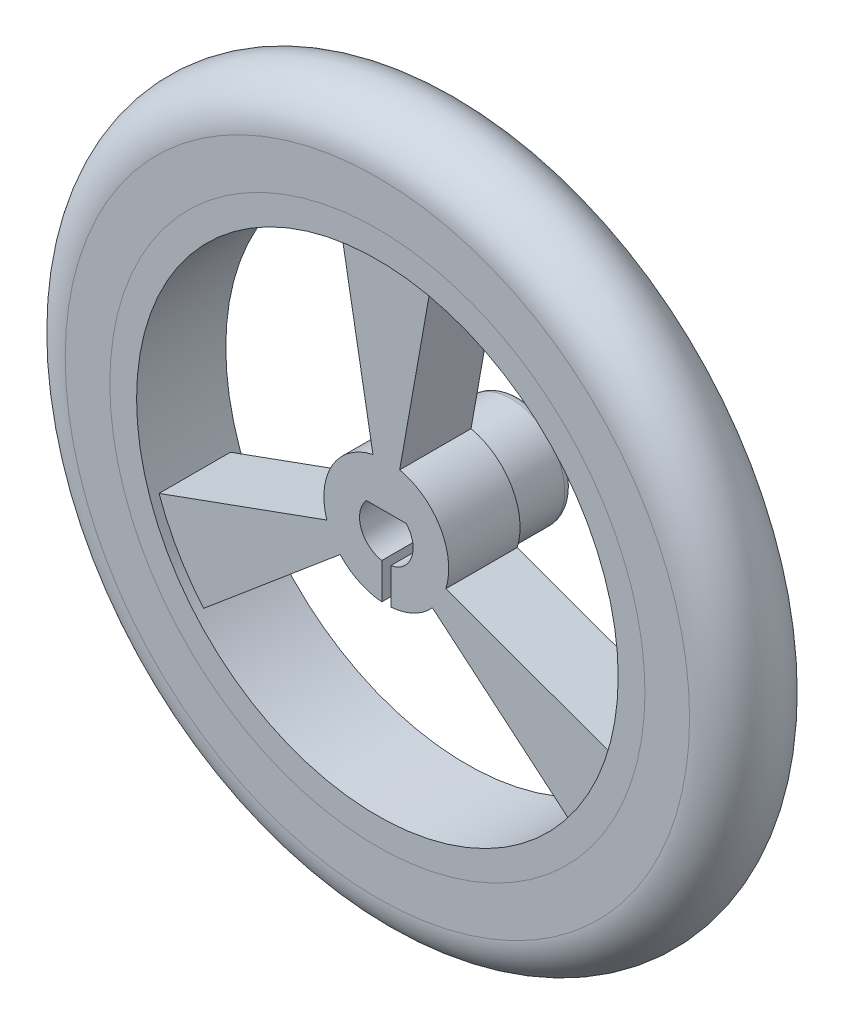
SolidWorks part; units mm, degrees
other "tire"
other "wheel"
ref_plane "Přední rovina" through (0, 0, 0) normal (0, 0, 1) x (1, 0, 0)
ref_plane "Horní rovina" through (0, 0, 0) normal (0, 1, 0) x (1, 0, 0)
ref_plane "Pravá rovina" through (0, 0, 0) normal (1, 0, 0) x (0, 0, -1)
sketch "Skica2" plane through (0, 0, 0) normal (1, 0, 0) x (0, 0, -1)
  line L0 (-2, 13.5) -> (-2, 0)
  line L1 (-1, 18) -> (1, 18)
  line L2 (1, 18) -> (1, 15)
  line L3 (1, 15) -> (2.5, 15)
  line L4 (2.5, 15) -> (2.5, 13.5)
  line L5 (2.5, 13.5) -> (2, 13.5)
  line L6 (5.5, 0) -> (-2, 0)
  line L7 (2, 13.5) -> (2, 3)
  line L8 (2, 3) -> (5, 3)
  line L9 (5.5, 2.5) -> (5.5, 0)
  line L10 (-36.9889, 0) -> (36.9889, 0) construction
  line L11 (0, 0) -> (0, 62.8313) construction
  line L13 (-2.5, 13.5) -> (-2, 13.5)
  line L14 (-2.5, 15) -> (-2.5, 13.5)
  line L15 (-1, 15) -> (-2.5, 15)
  line L16 (-1, 18) -> (-1, 15)
  arc A0 (5, 3) -> (5.5, 2.5) centre (5, 2.5) cw
  point P22 (0, 18)
  dimension "D9" = 0.5
  dimension "D1" = 36
  dimension "D2" = 5
  dimension "D3" = 3
  dimension "D4" = 4
  dimension "D5" = 1.5
  dimension "D6" = 6
  dimension "D7" = 8
  dimension "D8" = 1.5
revolve "Rotovat1" add sketch "Skica2" angle 360 about L10
sketch "Skica3" plane through (0, 0, 2) normal (0, 0, 1) x (1, 0, 0)
  line L0 (12.7391, -4.4682) -> (3.3357, -1.0598)
  line L1 (0, 0) -> (0, 29.5863) construction
  line L2 (-2.5, 13.2665) -> (-0.75, 3.4187)
  line L3 (10.2391, -8.7983) -> (2.5857, -2.3589)
  line L4 (-10.2391, -8.7983) -> (-2.5857, -2.3589)
  line L5 (-12.7391, -4.4682) -> (-3.3357, -1.0598)
  line L9 (2.5, 13.2665) -> (0.75, 3.4187)
  circle A0 centre (0, 0) radius 13.5 construction
  arc A1 (12.7391, -4.4682) -> (2.5, 13.2665) centre (0, 0) ccw
  arc A2 (-2.5, 13.2665) -> (-12.7391, -4.4682) centre (0, 0) ccw
  arc A3 (3.3357, -1.0598) -> (0.75, 3.4187) centre (0, 0) ccw
  arc A4 (-2.5857, -2.3589) -> (2.5857, -2.3589) centre (0, 0) ccw
  arc A5 (-10.2391, -8.7983) -> (10.2391, -8.7983) centre (0, 0) ccw
  arc A29 (-0.75, 3.4187) -> (-3.3357, -1.0598) centre (0, 0) ccw
  point P10 (-0.75, 3.4187)
  point P13 (0.75, 3.4187)
  dimension "D1" = 7
  dimension "D2" = 1.5
  dimension "D4" = 3
  dimension "D3" = 5
extrude "Odebrat vysunutím1" cut sketch "Skica3" against normal through all
sketch "Skica4" plane through (0, 0, 2) normal (0, 0, 1) x (1, 0, 0)
  line L0 (-1.118, 1) -> (1.118, 1)
  line L1 (0, 0) -> (0, -11.6723) construction
  line L2 (-0.25, -1.479) -> (-0.25, -4.8326)
  line L3 (0.25, -1.479) -> (0.25, -4.8326)
  line L4 (-0.25, -4.8326) -> (0.25, -4.8326)
  arc A0 (-1.118, 1) -> (-0.25, -1.479) centre (0, 0) ccw
  arc A1 (0.25, -1.479) -> (1.118, 1) centre (0, 0) ccw
  dimension "D1" = 3
  dimension "D2" = 2.5
  dimension "D3" = 0.5
extrude "Odebrat vysunutím2" cut sketch "Skica4" against normal through all
sketch "Skica5" plane through (0, 0, 0) normal (1, 0, 0) x (0, 0, -1)
  line L0 (-2.5, 15) -> (-2.5, 17.5)
  line L2 (2.5, 17.5) -> (2.5, 15)
  line L3 (-1, 15) -> (-2.5, 15) construction
  line L4 (-1, 18) -> (-1, -18) construction
  line L5 (1, 18) -> (-1, 18) construction
  line L6 (1, -18) -> (1, 18) construction
  line L7 (2.5, 15) -> (1, 15) construction
  line L8 (-1, 15) -> (-2.5, 15)
  line L9 (-1, 18) -> (-1, 15)
  line L10 (1, 18) -> (-1, 18)
  line L11 (1, 15) -> (1, 18)
  line L12 (2.5, 15) -> (1, 15)
  line L13 (0, 0) -> (18.2922, 0) construction
  arc A0 (-2.5, 17.5) -> (2.5, 17.5) centre (0, 17.5) cw
  dimension "D1" = 40
revolve "Rotovat2" add sketch "Skica5" angle 360 about L13
